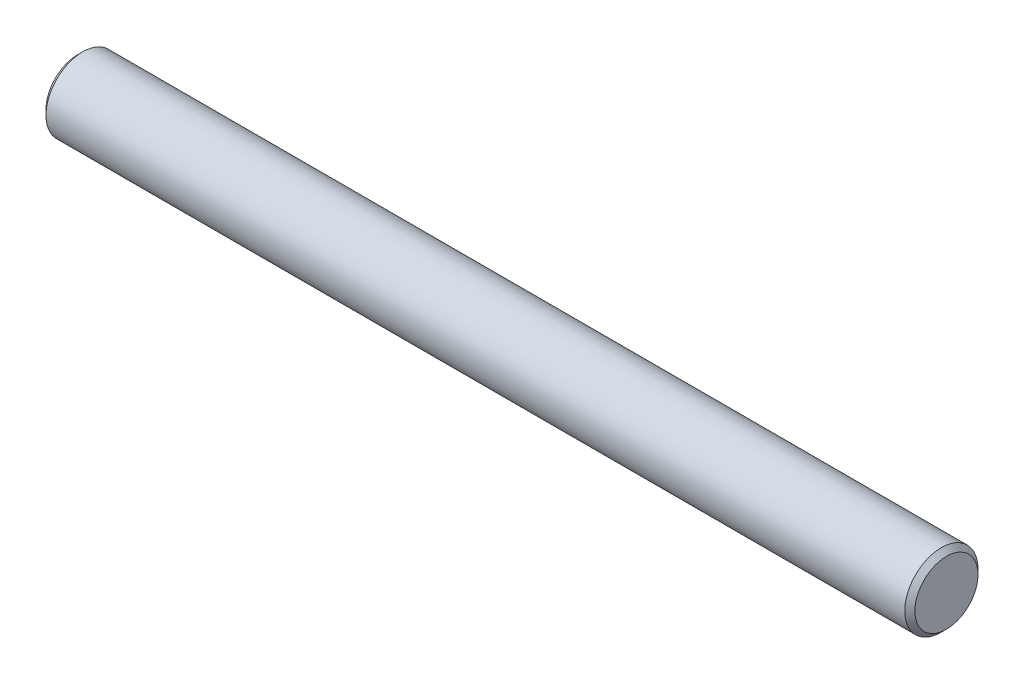
SolidWorks part; units mm, degrees
material "Acier allié inoxydable"
ref_plane "Plan de face" through (0, 0, 0) normal (0, 0, 1) x (1, 0, 0)
ref_plane "Plan de dessus" through (0, 0, 0) normal (0, 1, 0) x (1, 0, 0)
ref_plane "Plan de droite" through (0, 0, 0) normal (1, 0, 0) x (0, 0, -1)
other "L"
sketch "Esquisse1" plane through (0, 0, 0) normal (1, 0, 0) x (0, 0, -1)
  circle A0 centre (0, 0) radius 1.45
  dimension "D1" = 2.9
extrude "Boss.-Extru.1" add sketch "Esquisse1" along normal mid plane 34.4
chamfer "Chanfrein1" distance 0.2 angle 45 2 edges at (17.2, 0, -1.45) (-17.2, 0, -1.45)
